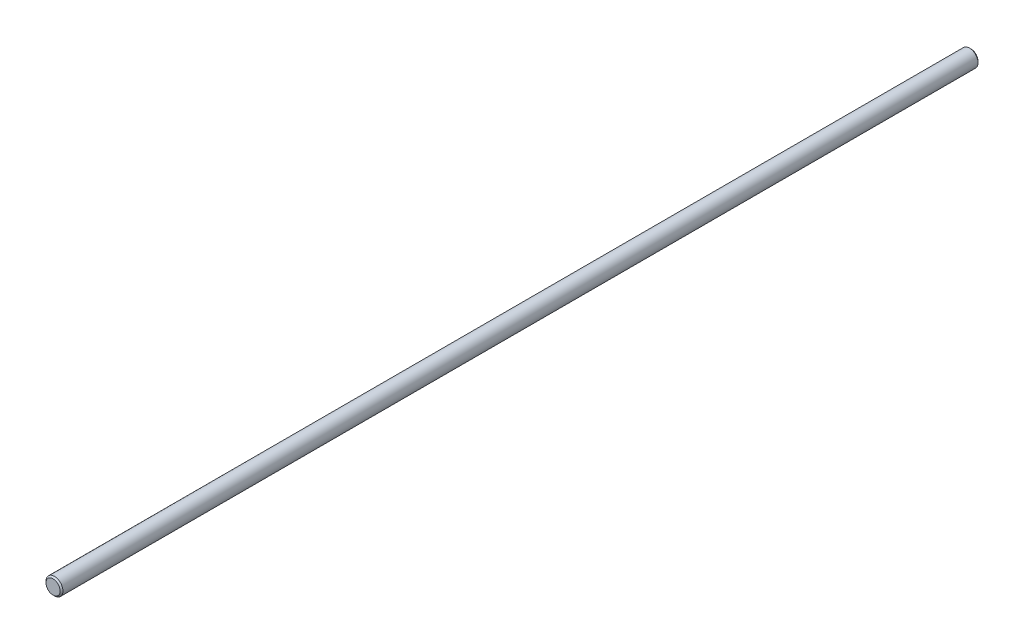
SolidWorks part; units mm, degrees
ref_plane "Front Plane" through (0, 0, 0) normal (0, 0, 1) x (1, 0, 0)
ref_plane "Top Plane" through (0, 0, 0) normal (0, 1, 0) x (1, 0, 0)
ref_plane "Right Plane" through (0, 0, 0) normal (1, 0, 0) x (0, 0, -1)
sketch "Sketch1" plane through (0, 0, 0) normal (0, 0, 1) x (1, 0, 0)
  circle A0 centre (0, 0) radius 6
  dimension "D1" = 12
extrude "Boss-Extrude1" add sketch "Sketch1" along normal mid plane 650
chamfer "Chamfer1" distance 1 angle 45 2 edges at (6, 0, 325) (6, 0, -325)
